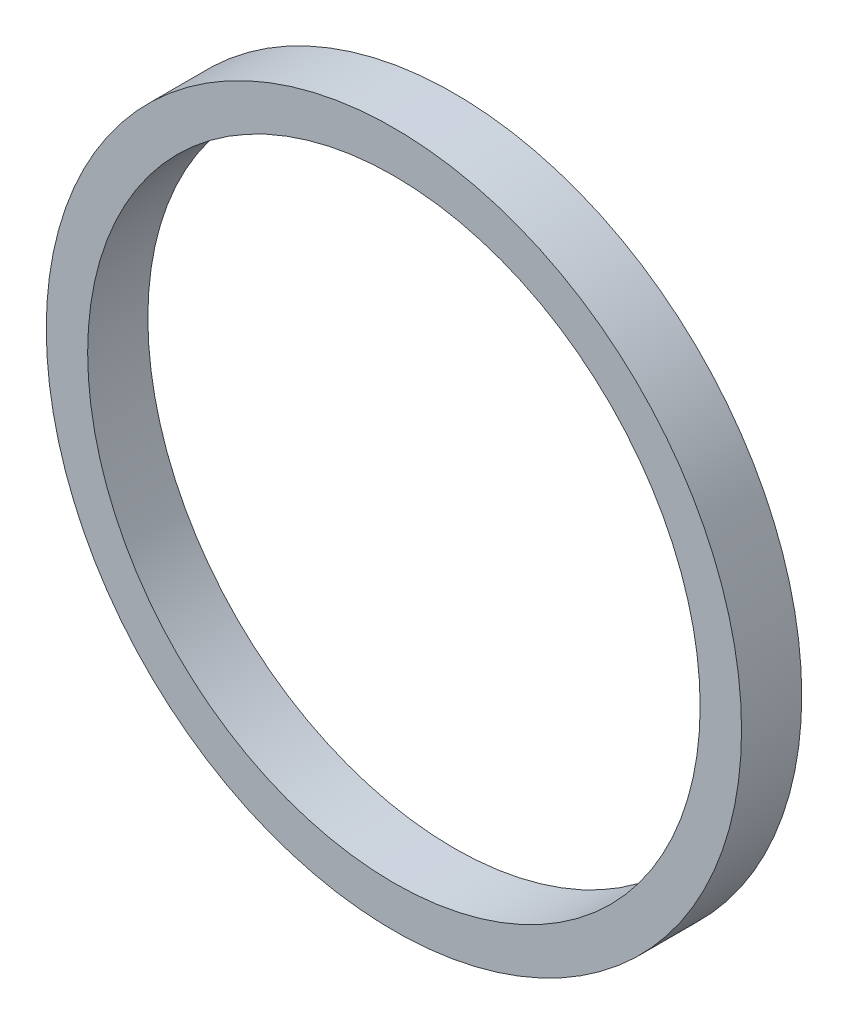
SolidWorks part; units mm, degrees
material "ABS"
ref_plane "Front Plane" through (0, 0, 0) normal (0, 0, 1) x (1, 0, 0)
ref_plane "Top Plane" through (0, 0, 0) normal (0, 1, 0) x (1, 0, 0)
ref_plane "Right Plane" through (0, 0, 0) normal (1, 0, 0) x (0, 0, -1)
sketch "Sketch1" plane through (0, 0, 0) normal (0, 0, 1) x (1, 0, 0)
  circle A0 centre (0, 0) radius 5.0875
  circle A1 centre (0, 0) radius 5.775
  dimension "D1" = 10.175
  dimension "D2" = 11.55
extrude "Boss-Extrude1" add sketch "Sketch1" along normal blind 1
equation "\"RingPinShaft\"= 5.05"
equation "\"CenterBearingOut\"=32.05"
equation "\"RingPostIn\"=5.15"
equation "\"CamBearingOut\"=15.1"
equation "\"DiskOutputShaft\"=10.1"
equation "\"CenterShaft\"=25.2"
equation "\"Eccentricity\"=2"
equation "\"CycCamShaft\"=10.05"
equation "\"D1@Sketch1\"=\"CycCamShaft\" + 0.125"
equation "\"D2@Sketch1\"=\"CycCamShaft\"+1.5"
